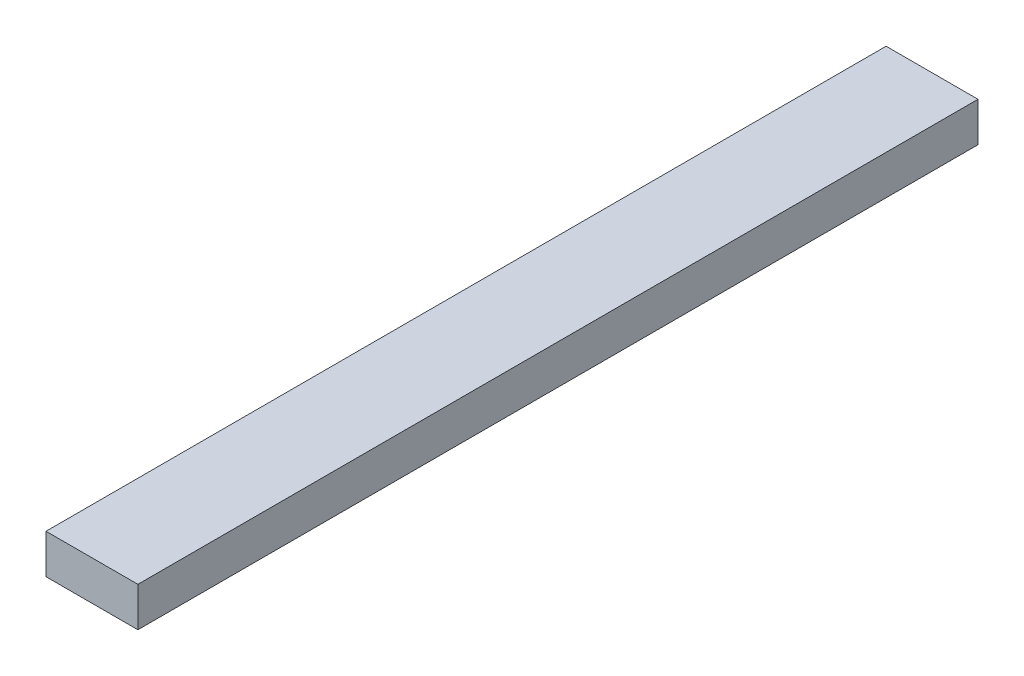
SolidWorks part; units mm, degrees
material "Pine"
ref_plane "Front Plane" through (0, 0, 0) normal (0, 0, 1) x (1, 0, 0)
ref_plane "Top Plane" through (0, 0, 0) normal (0, 1, 0) x (1, 0, 0)
ref_plane "Right Plane" through (0, 0, 0) normal (1, 0, 0) x (0, 0, -1)
sketch "Sketch1" plane through (0, 0, 0) normal (0, 0, 1) x (1, 0, 0)
  line L1 (44.45, -19.05) -> (-44.45, -19.05)
  line L2 (44.45, -19.05) -> (44.45, 19.05)
  line L3 (44.45, 19.05) -> (-44.45, 19.05)
  line L4 (-44.45, -19.05) -> (-44.45, 19.05)
  line L5 (44.45, -19.05) -> (-44.45, 19.05) construction
  line L6 (44.45, 19.05) -> (-44.45, -19.05) construction
  point P0 (0, 0)
  dimension "D1" = 88.9
  dimension "D2" = 38.1
extrude "Boss-Extrude1" add sketch "Sketch1" along normal blind 812.8 contours L4 L3 L2 L1
